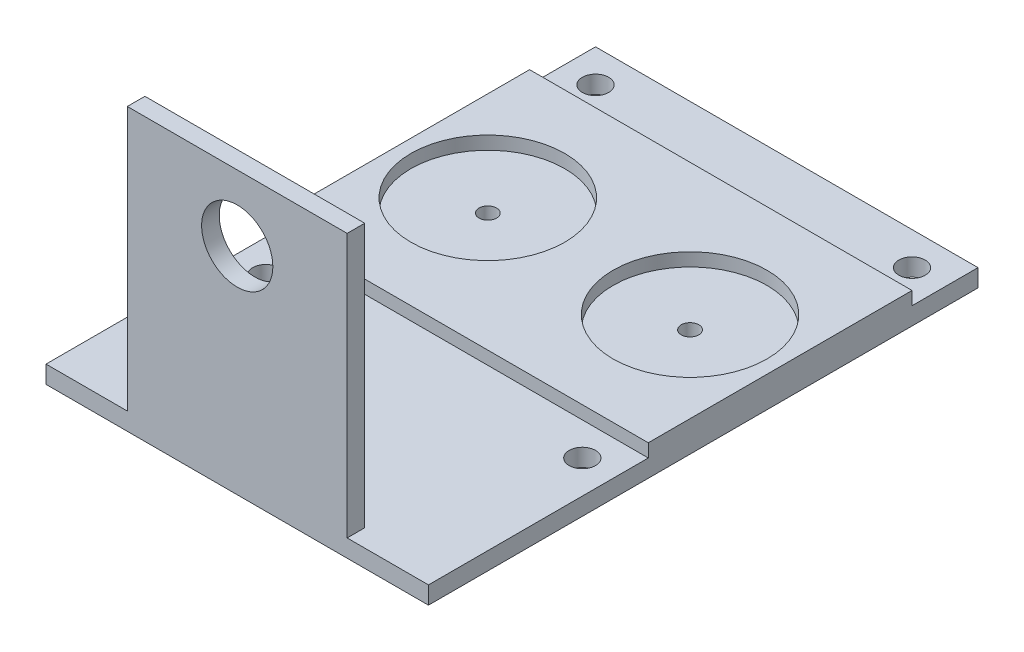
SolidWorks part; units mm, degrees
material "1060 合金"
ref_plane "前视" through (0, 0, 0) normal (0, 0, 1) x (1, 0, 0)
ref_plane "上视" through (0, 0, 0) normal (0, 1, 0) x (1, 0, 0)
ref_plane "右视" through (0, 0, 0) normal (1, 0, 0) x (0, 0, -1)
sketch "草图1" plane through (0, 0, 0) normal (0, 1, 0) x (1, 0, 0)
  line L0 (-43.5, 45) -> (43.5, 45)
  line L1 (-43.5, 45) -> (-43.5, -45)
  line L2 (-43.5, -45) -> (43.5, -45)
  line L3 (43.5, 45) -> (43.5, -45)
  line L4 (-43.5, 0) -> (43.5, 0) construction
  line L5 (0, -45) -> (0, 45) construction
  line L8 (-43.5, -45) -> (-43.5, -80)
  line L9 (-43.5, -80) -> (43.5, -80)
  line L10 (43.5, -45) -> (43.5, -80)
  circle A0 centre (-36, -37.5) radius 3
  circle A1 centre (36, -37.5) radius 3
  circle A2 centre (-36, 37.5) radius 3
  circle A3 centre (36, 37.5) radius 3
  dimension "D3" = 6
  dimension "D4" = 6
  dimension "D5" = 6
  dimension "D6" = 6
  dimension "D1" = 90
  dimension "D2" = 87
  dimension "D7" = 7.5
  dimension "D8" = 7.5
  dimension "D9" = 7.5
  dimension "D10" = 7.5
  dimension "D11" = 125
extrude "凸台-拉伸1" add sketch "草图1" along normal blind 4 contours L3 L0 L1 L2 A3 A2 A1 A0 | L10 L2 L8 L9
sketch "草图3" plane through (0, 4, 0) normal (0, 1, 0) x (1, 0, 0)
  line L0 (-43.5, 30) -> (43.5, 30)
  line L1 (-43.5, 30) -> (-43.5, -30)
  line L2 (-43.5, -30) -> (43.5, -30)
  line L3 (43.5, 30) -> (43.5, -30)
  line L4 (43.5, 45) -> (43.5, -80) construction
  line L5 (-43.5, 0) -> (43.5, 0) construction
  line L6 (-43.5, 45) -> (-43.5, -80) construction
  circle A0 centre (-23, 0) radius 17.5
  circle A1 centre (23, 0) radius 17.5
  dimension "D2" = 35
  dimension "D3" = 35
  dimension "D1" = 60
  dimension "D4" = 20.5
  dimension "D5" = 20.5
extrude "凸台-拉伸2" add sketch "草图3" along normal blind 3
sketch "草图4" plane through (0, 4, 0) normal (0, 1, 0) x (1, 0, 0)
  circle A0 centre (23, 0) radius 2
  circle A1 centre (-23, 0) radius 2
  dimension "D1" = 4
  dimension "D2" = 4
extrude "切除-拉伸1" cut sketch "草图4" against normal through all
sketch "草图5" plane through (0, 0, 80) normal (0, 0, 1) x (1, 0, 0)
  line L0 (-43.5, 4) -> (43.5, 4) construction
  line L1 (25, 4) -> (-25, 4)
  line L2 (25, 4) -> (25, 64)
  line L3 (25, 64) -> (-25, 64)
  line L4 (-25, 4) -> (-25, 64)
  line L5 (-43.5, 4) -> (-25, 4) construction
  line L6 (25, 4) -> (43.5, 4) construction
  circle A0 centre (0, 49) radius 8.1
  dimension "D3" = 16.2
  dimension "D1" = 50
  dimension "D2" = 60
  dimension "D4" = 45
extrude "凸台-拉伸3" add sketch "草图5" against normal blind 4
